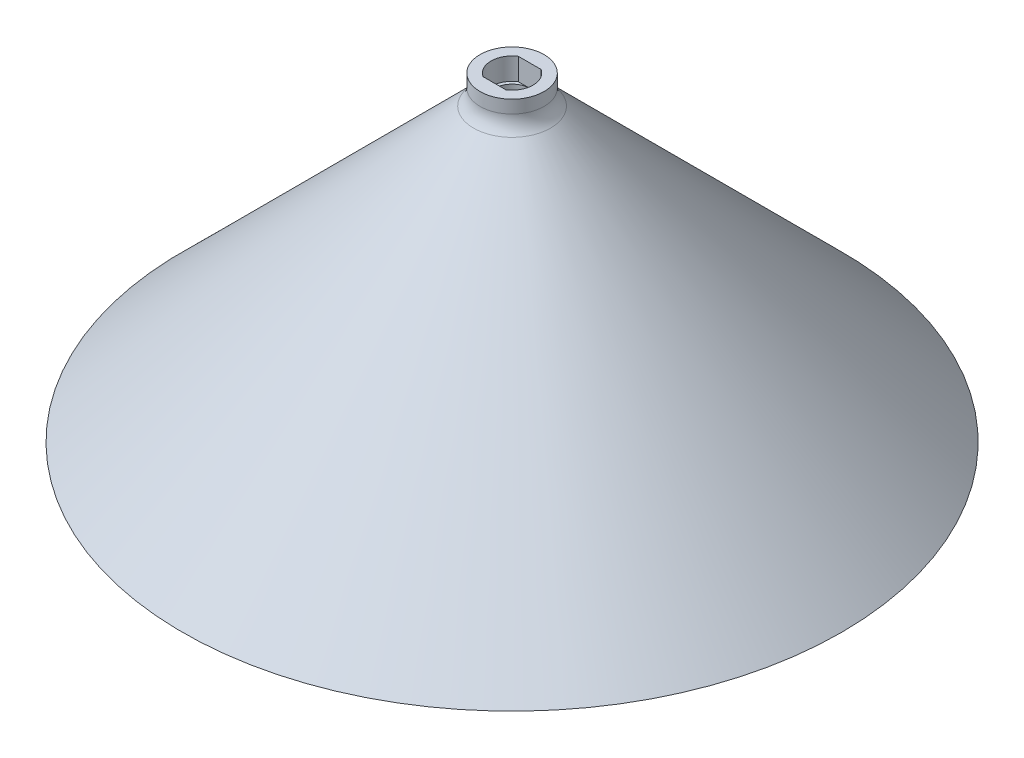
SolidWorks part; units mm, degrees
ref_plane "Front Plane" through (0, 0, 0) normal (0, 0, 1) x (1, 0, 0)
ref_plane "Top Plane" through (0, 0, 0) normal (0, 1, 0) x (1, 0, 0)
ref_plane "Right Plane" through (0, 0, 0) normal (1, 0, 0) x (0, 0, -1)
sketch "Sketch1" plane through (0, 0, 0) normal (0, 1, 0) x (1, 0, 0)
  line L0 (-5.168, 8.0011) -> (5.168, 8.0011)
  line L1 (-5.168, -8.0011) -> (5.168, -8.0011)
  arc A0 (-5.168, 8.0011) -> (-5.168, -8.0011) centre (0, 0) ccw
  arc A1 (5.168, -8.0011) -> (5.168, 8.0011) centre (0, 0) ccw
  circle A2 centre (0, 0) radius 14.525
  dimension "D1" = 19.05
  dimension "D3" = 5
  dimension "D2" = 10.336
extrude "Keyed portion adapter" add sketch "Sketch1" along normal blind 10
sketch "Sketch2" plane through (0, 0, 0) normal (0, -1, 0) x (1, 0, 0)
  line L0 (-5.168, 8.0011) -> (5.168, 8.0011) construction
  circle A0 centre (0, 0) radius 8.0011
  circle A2 centre (0, 0) radius 14.525
  circle A3 centre (0, 0) radius 14.525
  dimension "D1" = 0
extrude "Stopper (on threaded portion of piston)" add sketch "Sketch2" along normal blind 10
sketch "Sketch3" plane through (0, 0, 0) normal (0, 0, 1) x (1, 0, 0)
  line L0 (8.0011, -10) -> (8.0011, 0)
  line L1 (8.0011, 0) -> (14.525, 0)
  line L2 (14.525, -10) -> (14.525, 10) construction
  line L3 (14.525, 0) -> (149.525, -135)
  line L4 (149.525, -135) -> (133.0011, -135)
  line L5 (133.0011, -135) -> (8.0011, -10)
  line L6 (0, 0) -> (0, -135) construction
  dimension "D1" = 125
  dimension "D2" = 125
revolve "Conical base" add sketch "Sketch3" angle 360 about L6
fillet "Piston holder to conical base adapter" radius 10 1 edges at (14.525, 0, 0)
